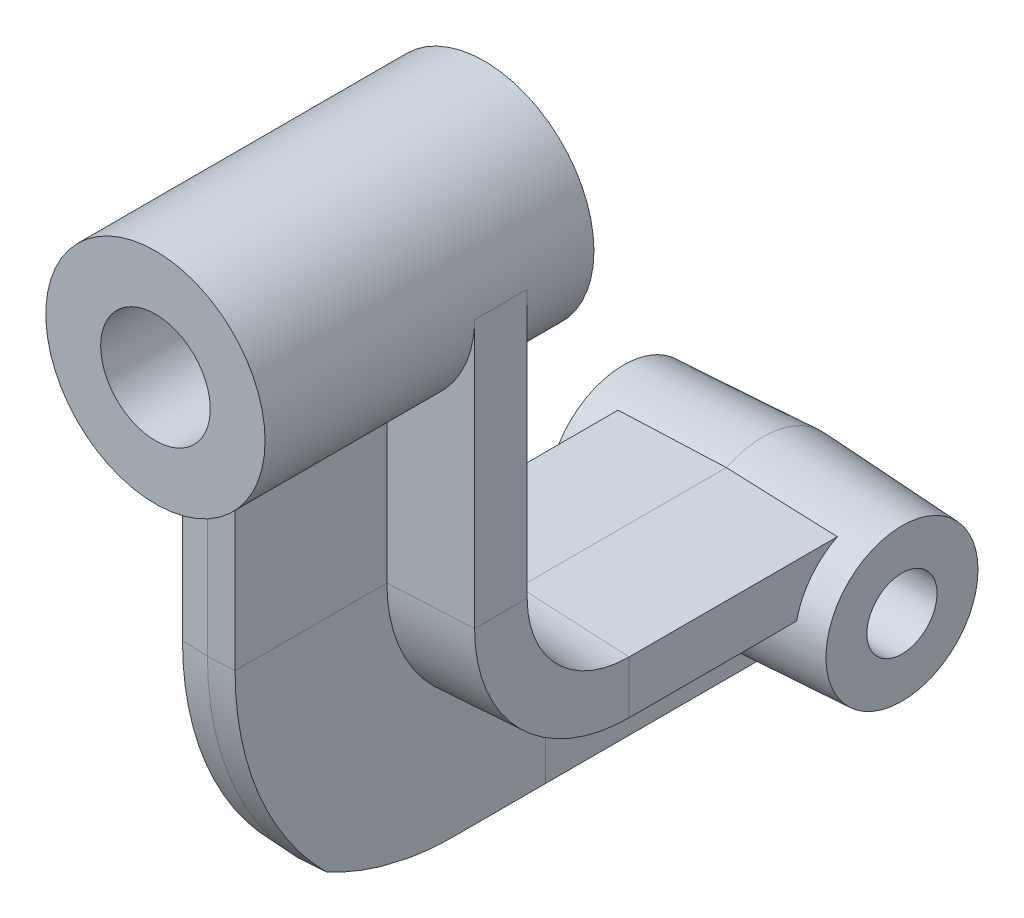
SolidWorks part; units mm, degrees
ref_plane "Front Plane" through (0, 0, 0) normal (0, 0, 1) x (1, 0, 0)
ref_plane "Top Plane" through (0, 0, 0) normal (0, 1, 0) x (1, 0, 0)
ref_plane "Right Plane" through (0, 0, 0) normal (1, 0, 0) x (0, 0, -1)
sketch "Sketch1" plane through (0, 0, 0) normal (0, 0, 1) x (1, 0, 0)
  circle A0 centre (0, 0) radius 25
  dimension "D1" = 50
extrude "Boss-Extrude1" add sketch "Sketch1" along normal blind 75
sketch "Sketch2" plane through (0, 0, 0) normal (1, 0, 0) x (0, 0, -1)
  circle A0 centre (63.5, -100) radius 19
  dimension "D1" = 38
  dimension "D2" = 63.5
  dimension "D3" = 100
extrude "Boss-Extrude2" add sketch "Sketch2" along normal mid plane 63.5 draft 3 separate body
sketch "Sketch5" plane through (0, 0, 0) normal (1, 0, 0) x (0, 0, -1)
  line L0 (63.5, -81) -> (8, -81)
  line L1 (-12, -61) -> (-12, 0)
  line L2 (63.5, -119) -> (-9, -119)
  line L3 (-69, -59) -> (-69, 0)
  circle A0 centre (63.5, -100) radius 19 construction
  circle A1 centre (63.5, -100) radius 19 construction
  arc A2 (8, -81) -> (-12, -61) centre (8, -61) cw
  arc A3 (-9, -119) -> (-69, -59) centre (-9, -59) cw
  dimension "D3" = 20
  dimension "D4" = 60
  dimension "D1" = 12
  dimension "D2" = 57
sketch "Sketch6" plane through (0, 0, 0) normal (0, 1, 0) x (1, 0, 0)
  line L0 (0, -63.1495) -> (0, -122.875) construction
  line L1 (0, -69) -> (0, -9) construction
  line L2 (0, -63.1495) -> (-6, -62.8351)
  line L3 (-6, -62.8351) -> (-6, -28.2161)
  line L4 (-6, -28.2161) -> (-25, -27.2203)
  line L5 (-25, -27.2203) -> (-25, -15.2203)
  line L6 (-25, -15.2203) -> (0, -13.9101)
  line L7 (25, -15.2203) -> (0, -13.9101)
  line L8 (25, -27.2203) -> (25, -15.2203)
  line L9 (6, -28.2161) -> (25, -27.2203)
  line L10 (6, -62.8351) -> (6, -28.2161)
  line L11 (0, -63.1495) -> (6, -62.8351)
  dimension "D1" = 12
  dimension "D2" = 50
  dimension "D3" = 3
  dimension "D4" = 3
  dimension "D5" = 12
  dimension "D6" = 3
sweep "Sweep2" add profiles "Sketch6" path "Sketch5"
sketch "Sketch11" plane through (6, 0, 0) normal (1, 0, 0) x (0, 0, -1)
  line L0 (63.5, -118.6856) -> (-12.8649, -118.6856)
  line L1 (63.5, -131.8351) -> (63.5, -118.6856) construction
  line L2 (63.5, -118.6856) -> (63.5, -131.8351)
  line L3 (63.5, -131.8351) -> (8, -131.8351)
  line L6 (63.5, -131.8351) -> (8, -131.8351) construction
  arc A0 (45.023, -97.2161) -> (63.5, -118.6856) centre (63.5, -100) ccw construction
  arc A1 (-62.8351, -61) -> (8, -131.8351) centre (8, -61) ccw construction
  arc A2 (-12.8649, -118.6856) -> (-42.088, -111.088) centre (-12.8649, -58.6856) cw
  arc A3 (8, -131.8351) -> (-42.088, -111.088) centre (8, -61) cw
  point P13 (-33.1094, -118.6856)
  point P16 (0, 0)
  point P18 (0, 0)
  point P20 (63.5, -131.8351)
  dimension "D1" = 60
extrude "Cut-Extrude2" cut sketch "Sketch11" against normal through all
sketch "Sketch13" plane through (6, 0, 0) normal (1, 0, 0) x (0, 0, -1)
  line L0 (-45.2006, -110.2958) -> (-42.088, -111.088)
  line L2 (-23.4613, -117.7424) -> (44.8478, -128.3473)
  line L3 (44.8478, -128.3473) -> (71.0182, -129.97)
  line L4 (71.0182, -129.97) -> (72.3281, -135.7502)
  line L5 (72.3281, -135.7502) -> (-4.744, -135.7502)
  line L6 (-4.744, -135.7502) -> (-39.7166, -116.7551)
  line L7 (-39.7166, -116.7551) -> (-45.2006, -110.2958)
  line L8 (-29.6678, -116.2847) -> (-23.4613, -117.7424)
  arc A0 (-42.088, -111.088) -> (-12.8649, -118.6856) centre (-12.8649, -58.6856) ccw construction
  arc A1 (-42.088, -111.088) -> (-29.6678, -116.2847) centre (-12.8649, -58.6856) ccw
extrude "Cut-Extrude3" cut sketch "Sketch13" against normal through all
sketch "Sketch14" plane through (0, 0, 0) normal (0, 0, -1) x (-1, 0, 0)
  circle A0 centre (0, 0) radius 12.5
  dimension "D1" = 25
extrude "Cut-Extrude4" cut sketch "Sketch14" against normal through all
sketch "Sketch16" plane through (-31.75, 0, 0) normal (-1, 0, 0) x (0, 0, 1)
  circle A0 centre (-63.5, -100) radius 8
  dimension "D1" = 16
extrude "Cut-Extrude5" cut sketch "Sketch16" against normal through all
equation "\"63.50mmmm\"=75"
